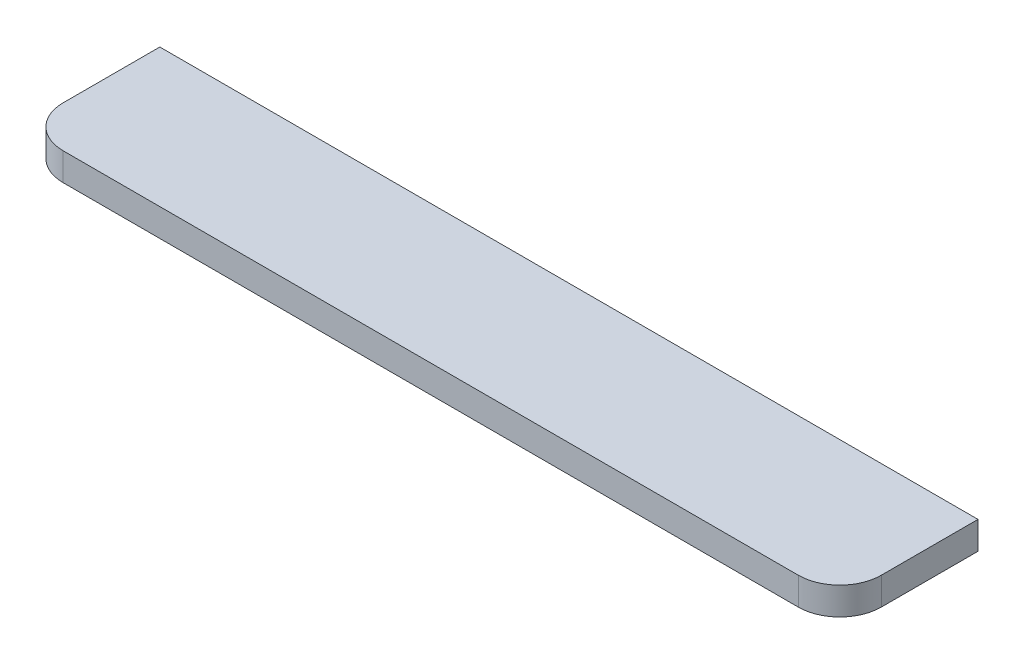
SolidWorks part; units mm, degrees
material "Plain Carbon Steel"
ref_plane "Front Plane" through (0, 0, 0) normal (0, 0, 1) x (1, 0, 0)
ref_plane "Top Plane" through (0, 0, 0) normal (0, 1, 0) x (1, 0, 0)
ref_plane "Right Plane" through (0, 0, 0) normal (1, 0, 0) x (0, 0, -1)
sketch "Sketch1" plane through (0, 0, 0) normal (0, 1, 0) x (1, 0, 0)
  line L1 (-148, 25) -> (148, 25)
  line L2 (-148, 25) -> (-148, -10)
  line L3 (-133, -25) -> (133, -25)
  line L4 (148, 25) -> (148, -10)
  line L5 (-148, 25) -> (148, -25) construction
  line L6 (-148, -25) -> (148, 25) construction
  arc A0 (133, -25) -> (148, -10) centre (133, -10) ccw
  arc A1 (-148, -10) -> (-133, -25) centre (-133, -10) ccw
  point P0 (0, 0)
  dimension "D3" = 15
  dimension "D1" = 50
  dimension "D2" = 296
extrude "Boss-Extrude1" add sketch "Sketch1" along normal blind 10 contours L1 L4 A0 L3 A1 L2
